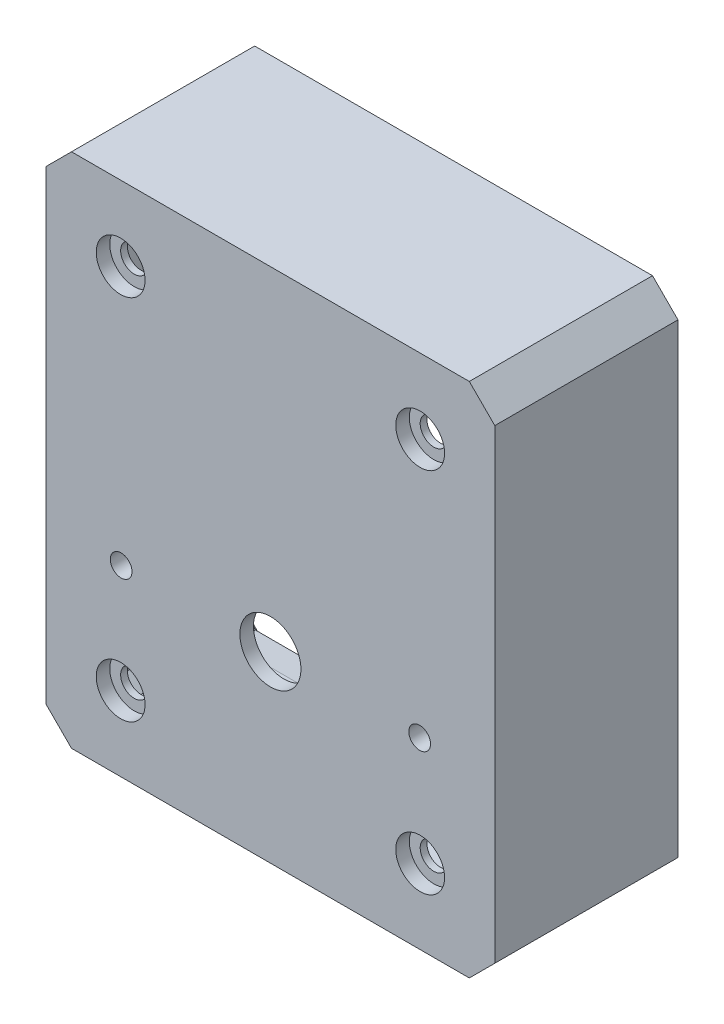
SolidWorks part; units mm, degrees
ref_plane "Ebene vorne" through (0, 0, 0) normal (0, 0, 1) x (1, 0, 0)
ref_plane "Ebene oben" through (0, 0, 0) normal (0, 1, 0) x (1, 0, 0)
ref_plane "Ebene rechts" through (0, 0, 0) normal (1, 0, 0) x (0, 0, -1)
sketch "Skizze1" plane through (0, 0, 0) normal (0, 0, 1) x (1, 0, 0)
  line L1 (0, 0) -> (60.15, 0)
  line L2 (0, 0) -> (0, 70.15)
  line L3 (0, 70.15) -> (60.15, 70.15)
  line L4 (60.15, 0) -> (60.15, 70.15)
  dimension "D1" = 60.15
  dimension "D2" = 70.15
extrude "Grundkörper" add sketch "Skizze1" along normal blind 24
chamfer "Fase1" distance 2 angle 45 4 edges at (60.15, 0, 12) (0, 0, 12) (0, 70.15, 12) (60.15, 70.15, 12)
shell "Wandung1" thickness 3
sketch "Skizze2" plane through (0, 0, 27) normal (0, 0, 1) x (1, 0, 0)
  line L0 (2, 0) -> (58.15, 0) construction
  line L2 (60.15, 24) -> (30.075, 24) construction
  line L3 (30.075, 24) -> (0, 24) construction
  line L4 (60.15, 2) -> (60.15, 68.15) construction
  line L5 (0, 68.15) -> (0, 2) construction
  circle A0 centre (30.075, 24) radius 4.5
  dimension "D1" = 9
  dimension "D2" = 24
extrude "Durchbruch Servo" cut sketch "Skizze2" against normal through all
sketch "Skizze4" plane through (0, 0, 24) normal (0, 0, -1) x (-1, 0, 0)
  line L0 (-30.075, 24) -> (-30.075, 14) construction
  line L5 (-41.075, 56) -> (-19.075, 56)
  line L6 (-41.075, 56) -> (-41.075, 14)
  line L7 (-41.075, 14) -> (-19.075, 14)
  line L8 (-19.075, 56) -> (-19.075, 14)
  dimension "D1" = 42
  dimension "D2" = 22
  dimension "D3" = 10
extrude "ServoFreischnitt" cut sketch "Skizze4" against normal offset from surface (1 mm away) 2 up to face at (34.575, 24, 27)
sketch "Skizze3" plane through (0, 0, 27) normal (0, 0, 1) x (1, 0, 0)
  line L18 (30.075, 24) -> (30.075, 46.6296) construction
  line L20 (30.075, 24) -> (6.2908, 24) construction
  line L21 (6.2908, 24) -> (30.075, 24) construction
  circle A32 centre (8.075, 24) radius 1.6
  circle A33 centre (52.075, 24) radius 1.6
  dimension "D3" = 44
  dimension "D6" = 3.2
  dimension "D7" = 3.2
  dimension "D4" = 22
sketch "Skizze7" plane through (0, 0, 27) normal (0, 0, 1) x (1, 0, 0)
  line L0 (30.075, 73.15) -> (30.075, -3) construction
  line L1 (59.3926, 73.15) -> (0.7574, 73.15) construction
  line L2 (0.7574, -3) -> (59.3926, -3) construction
  line L4 (-3, 69.3926) -> (-3, 0.7574) construction
  line L5 (-3, 35.075) -> (63.15, 35.075) construction
  line L6 (63.15, 0.7574) -> (63.15, 69.3926) construction
  circle A0 centre (8, 62.15) radius 2
  circle A1 centre (52.15, 62.15) radius 2
  circle A2 centre (52.15, 8) radius 2
  circle A3 centre (8, 8) radius 2
  dimension "D1" = 4
  dimension "D2" = 11
  dimension "D3" = 11
extrude "Schnitt-Linear austragen2" cut sketch "Skizze7" against normal up to next
sketch "Skizze8" plane through (0, 0, 27) normal (0, 0, 1) x (1, 0, 0)
  circle A0 centre (8, 62.15) radius 3.6
  circle A1 centre (52.15, 62.15) radius 3.6
  circle A2 centre (52.15, 8) radius 3.6
  circle A3 centre (8, 8) radius 3.6
  dimension "D1" = 7.2
  dimension "D2" = 7.2
  dimension "D3" = 7.2
  dimension "D4" = 7.2
extrude "Schnitt-Linear austragen3" cut sketch "Skizze8" against normal blind 2
extrude "Schnitt-Linear austragen5" cut sketch "Skizze3" against normal up to next
chamfer "Fase2" distance 5 angle 5 8 edges at (59.15, 1, 0) (30.075, 0, 0) (1, 1, 0) (0, 35.075, 0) (1, 69.15, 0) (30.075, 70.15, 0) (59.15, 69.15, 0) (60.15, 35.075, 0)
chamfer "Fase3" distance 1 angle 45 8 edges at (0.6907, 0.6907, 0) (-0.4374, 35.075, 0) (0.6907, 69.4593, 0) (30.075, 70.5874, 0) (59.4593, 69.4593, 0) (60.5874, 35.075, 0) (59.4593, 0.6907, 0) (30.075, -0.4374, 0)
